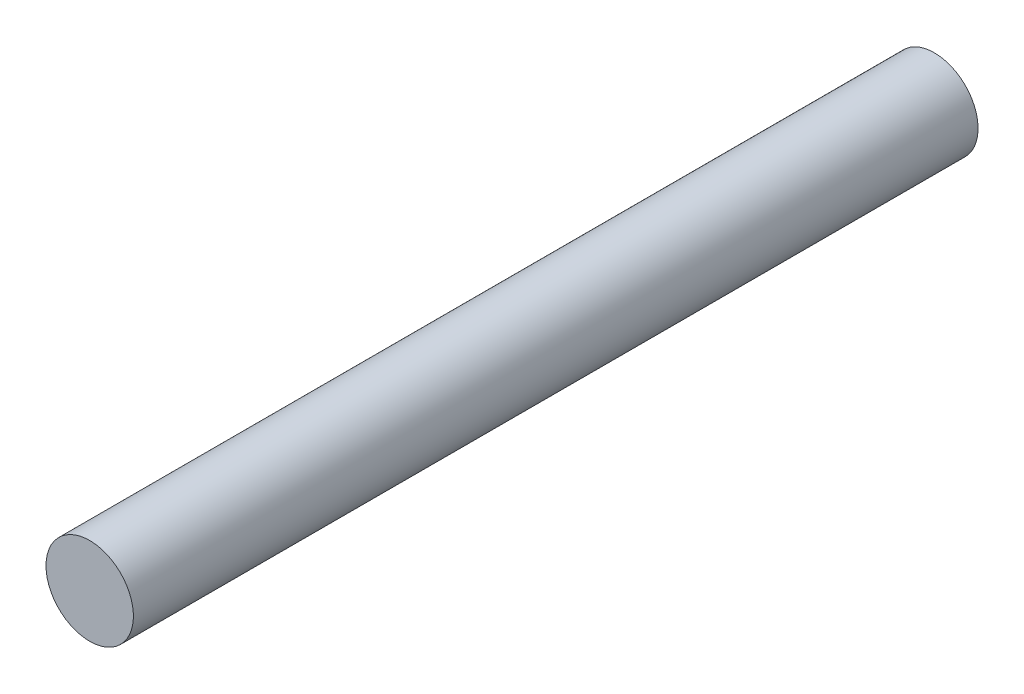
SolidWorks part; units mm, degrees
material "ｽﾃﾝﾚｽ鋼(ｸﾛﾑ)"
ref_plane "正面" through (0, 0, 0) normal (0, 0, 1) x (1, 0, 0)
ref_plane "平面" through (0, 0, 0) normal (0, 1, 0) x (1, 0, 0)
ref_plane "右側面" through (0, 0, 0) normal (1, 0, 0) x (0, 0, -1)
sketch "ｽｹｯﾁ1" plane through (0, 0, 0) normal (0, 0, 1) x (1, 0, 0)
  circle A0 centre (0, 0) radius 3
  dimension "D1" = 6
extrude "ﾎﾞｽ - 押し出し1" add sketch "ｽｹｯﾁ1" along normal blind 58
